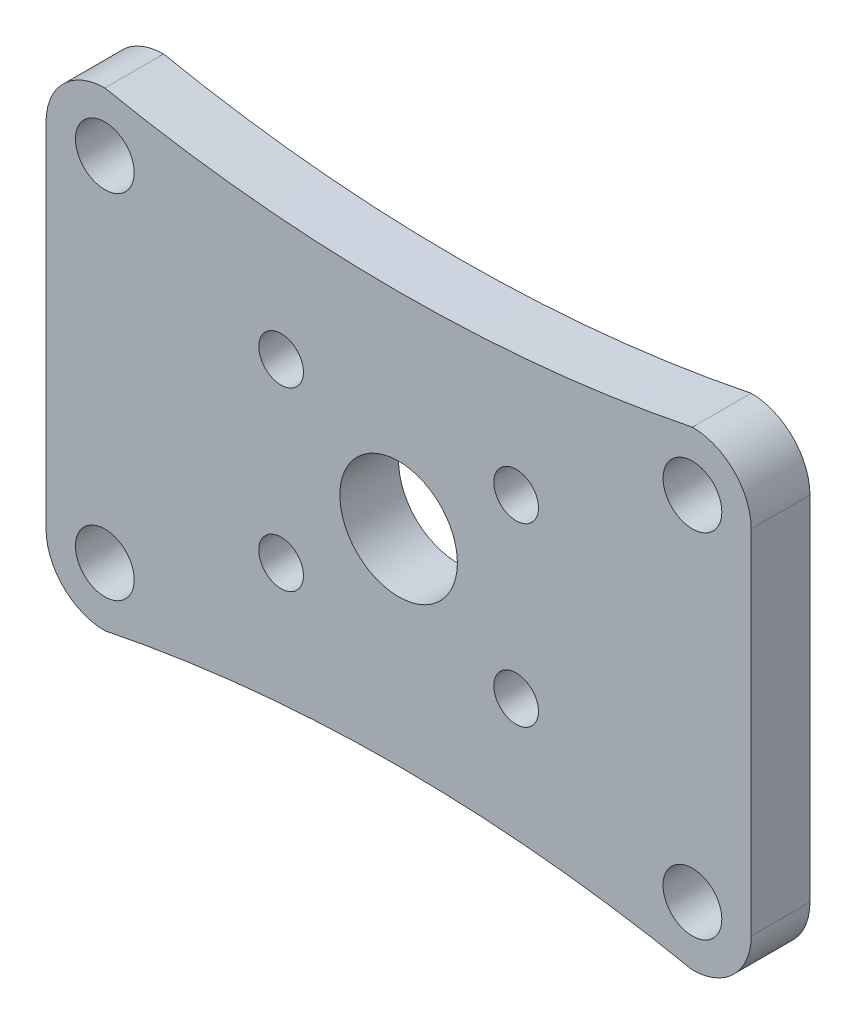
SolidWorks part; units mm, degrees
material "AISI 4130 Steel, normalized at 870C"
ref_plane "Front Plane" through (0, 0, 0) normal (0, 0, 1) x (1, 0, 0)
ref_plane "Top Plane" through (0, 0, 0) normal (0, 1, 0) x (1, 0, 0)
ref_plane "Right Plane" through (0, 0, 0) normal (1, 0, 0) x (0, 0, -1)
sketch "Sketch1" plane through (0, 0, 0) normal (0, 0, 1) x (1, 0, 0)
  line L0 (-388.7891, 181.1906) -> (-388.7891, 143.0906)
  line L1 (-312.5891, 181.1906) -> (-312.5891, 143.0906)
  circle A1 centre (-382.4391, 181.1906) radius 3.175
  circle A3 centre (-318.9391, 181.1906) radius 3.175
  circle A5 centre (-382.4391, 143.0906) radius 3.175
  circle A7 centre (-318.9391, 143.0906) radius 3.175
  arc A8 (-382.4391, 187.5406) -> (-388.7891, 181.1906) centre (-382.4391, 181.1906) ccw
  arc A9 (-388.7891, 143.0906) -> (-382.4391, 136.7406) centre (-382.4391, 143.0906) ccw
  arc A10 (-318.9391, 136.7406) -> (-312.5891, 143.0906) centre (-318.9391, 143.0906) ccw
  arc A11 (-312.5891, 181.1906) -> (-318.9391, 187.5406) centre (-318.9391, 181.1906) ccw
  arc A12 (-382.4391, 187.5406) -> (-318.9391, 187.5406) centre (-350.6891, 343.264) ccw
  arc A13 (-382.4391, 136.7406) -> (-318.9391, 136.7406) centre (-350.6891, -18.9828) cw
extrude "Boss-Extrude1" add sketch "Sketch1" along normal blind 6.35
sketch "Sketch3" plane through (0, 0, 6.35) normal (0, 0, 1) x (1, 0, 0)
  line L0 (-388.7891, 162.1406) -> (-312.5891, 162.1406) construction
  line L1 (-388.7891, 181.1906) -> (-388.7891, 143.0906) construction
  line L2 (-312.5891, 143.0906) -> (-312.5891, 181.1906) construction
  circle A0 centre (-350.6891, 162.1406) radius 6.35
  dimension "D1" = 12.7
extrude "Cut-Extrude1" cut sketch "Sketch3" against normal blind 6.35
sketch "Sketch4" plane through (0, 0, 6.35) normal (0, 0, 1) x (1, 0, 0)
  line L0 (-350.6891, 162.1406) -> (-350.6891, 171.6656) construction
  line L1 (-337.9891, 171.6656) -> (-363.3891, 171.6656) construction
  line L2 (-337.9891, 152.6156) -> (-363.3891, 152.6156) construction
  line L3 (-350.6891, 162.1406) -> (-359.211, 162.1406) construction
  circle A0 centre (-337.9891, 171.6656) radius 2.413
  circle A1 centre (-337.9891, 152.6156) radius 2.413
  circle A2 centre (-363.3891, 152.6156) radius 2.413
  circle A3 centre (-363.3891, 171.6656) radius 2.413
  dimension "D3" = 4.826
  dimension "D4" = 4.826
  dimension "D5" = 4.826
  dimension "D6" = 4.826
  dimension "D1" = 12.7
  dimension "D2" = 9.525
extrude "Cut-Extrude2" cut sketch "Sketch4" against normal blind 6.35
